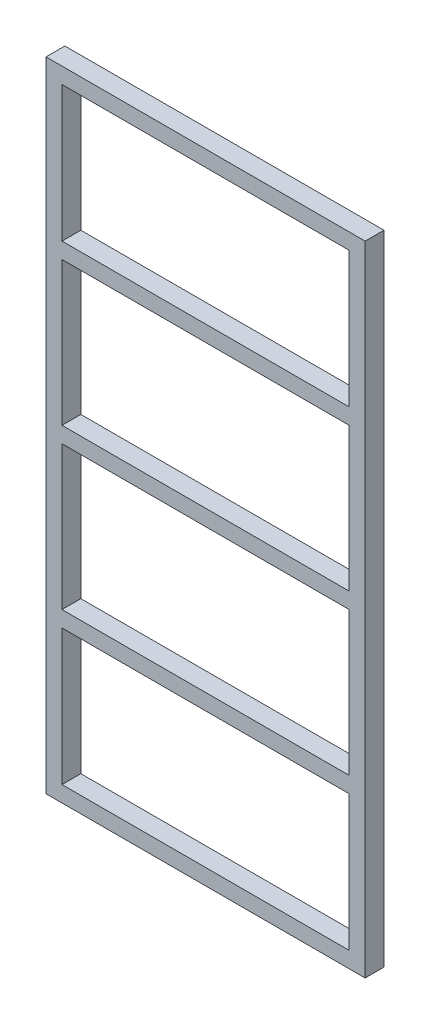
SolidWorks part; units mm, degrees
ref_plane "Front Plane" through (0, 0, 0) normal (0, 0, 1) x (1, 0, 0)
ref_plane "Top Plane" through (0, 0, 0) normal (0, 1, 0) x (1, 0, 0)
ref_plane "Right Plane" through (0, 0, 0) normal (1, 0, 0) x (0, 0, -1)
sketch "Sketch1" plane through (0, 0, 0) normal (0, 0, 1) x (1, 0, 0)
  line L0 (-22.86, 48.26) -> (22.86, 48.26)
  line L1 (-25.4, 50.8) -> (25.4, 50.8)
  line L2 (-25.4, 50.8) -> (-25.4, -50.8)
  line L3 (-25.4, -50.8) -> (25.4, -50.8)
  line L4 (25.4, 50.8) -> (25.4, -50.8)
  line L5 (-25.4, 50.8) -> (25.4, -50.8) construction
  line L6 (-25.4, -50.8) -> (25.4, 50.8) construction
  line L7 (22.86, 48.26) -> (22.86, 26.67)
  line L8 (-22.86, -48.26) -> (22.86, -48.26)
  line L9 (-22.86, 48.26) -> (-22.86, 26.67)
  line L10 (22.86, 0) -> (-22.86, 0) construction
  line L11 (22.86, 25.4) -> (-22.86, 25.4) construction
  line L12 (22.86, -25.4) -> (-22.86, -25.4) construction
  line L13 (22.86, 1.27) -> (-22.86, 1.27)
  line L14 (22.86, 26.67) -> (-22.86, 26.67)
  line L15 (22.86, -24.13) -> (-22.86, -24.13)
  line L16 (22.86, -1.27) -> (-22.86, -1.27)
  line L17 (22.86, 24.13) -> (-22.86, 24.13)
  line L18 (22.86, -26.67) -> (-22.86, -26.67)
  line L19 (-22.86, -1.27) -> (-22.86, -24.13)
  line L20 (22.86, -1.27) -> (22.86, -24.13)
  line L21 (-22.86, 48.26) -> (-22.86, -48.26) construction
  line L22 (-22.86, 24.13) -> (-22.86, 1.27)
  line L23 (22.86, 48.26) -> (22.86, -48.26) construction
  line L24 (22.86, 24.13) -> (22.86, 1.27)
  line L25 (-22.86, -26.67) -> (-22.86, -48.26)
  line L26 (22.86, -26.67) -> (22.86, -48.26)
  point P0 (0, 0)
  dimension "D1" = 50.8
  dimension "D2" = 101.6
  dimension "D3" = 2.54
  dimension "D4" = 25.4
  dimension "D5" = 25.4
  dimension "D6" = 1.27
  dimension "D7" = 1.27
extrude "Boss-Extrude1" add sketch "Sketch1" along normal blind 3
